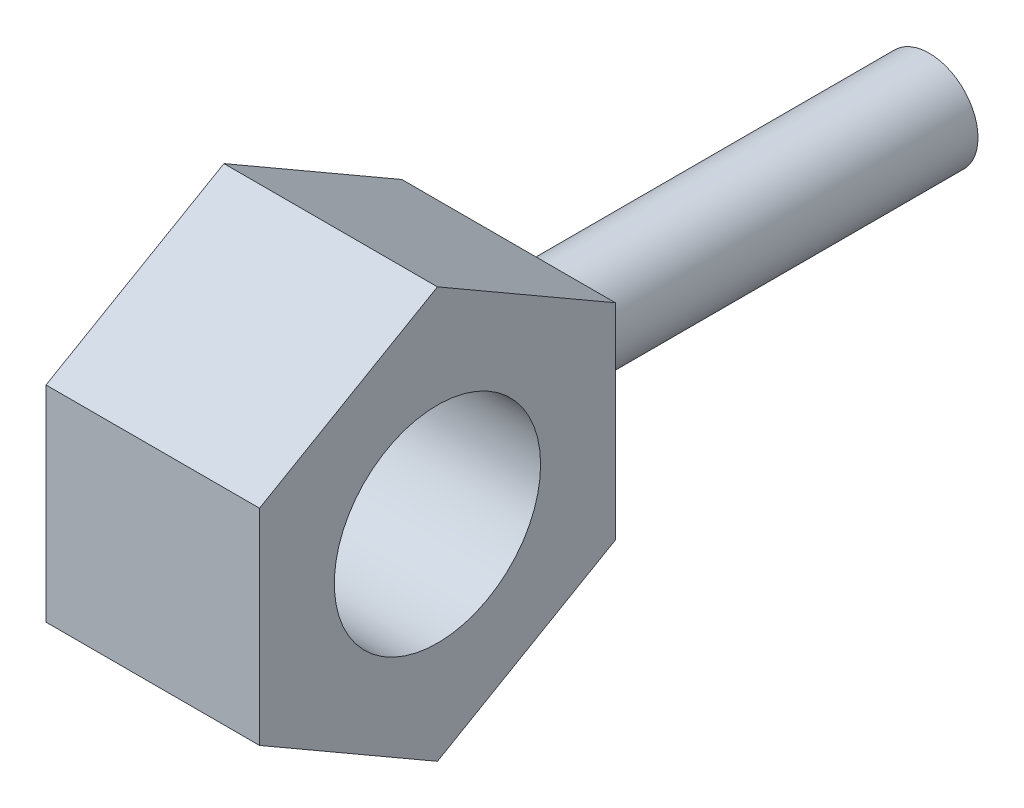
SolidWorks part; units mm, degrees
ref_plane "Alzado" through (0, 0, 0) normal (0, 0, 1) x (1, 0, 0)
ref_plane "Planta" through (0, 0, 0) normal (0, 1, 0) x (1, 0, 0)
ref_plane "Vista lateral" through (0, 0, 0) normal (1, 0, 0) x (0, 0, -1)
sketch "Croquis1" plane through (0, 0, 0) normal (1, 0, 0) x (0, 0, -1)
  line L1 (25, 14.4338) -> (0, 28.8675)
  line L2 (0, 28.8675) -> (-25, 14.4338)
  line L3 (-25, 14.4338) -> (-25, -14.4338)
  line L4 (-25, -14.4338) -> (0, -28.8675)
  line L5 (0, -28.8675) -> (25, -14.4338)
  line L6 (25, -14.4338) -> (25, 14.4338)
  circle A0 centre (0, 0) radius 14.4934
  circle A1 centre (0, 0) radius 25 construction
  dimension "D1" = 50
extrude "Saliente-Extruir1" add sketch "Croquis1" along normal blind 30
sketch "Croquis2" plane through (0, 0, -25) normal (0, 0, -1) x (-1, 0, 0)
  circle A0 centre (-14.0993, 0) radius 6.8497
extrude "Saliente-Extruir2" add sketch "Croquis2" along normal blind 60
